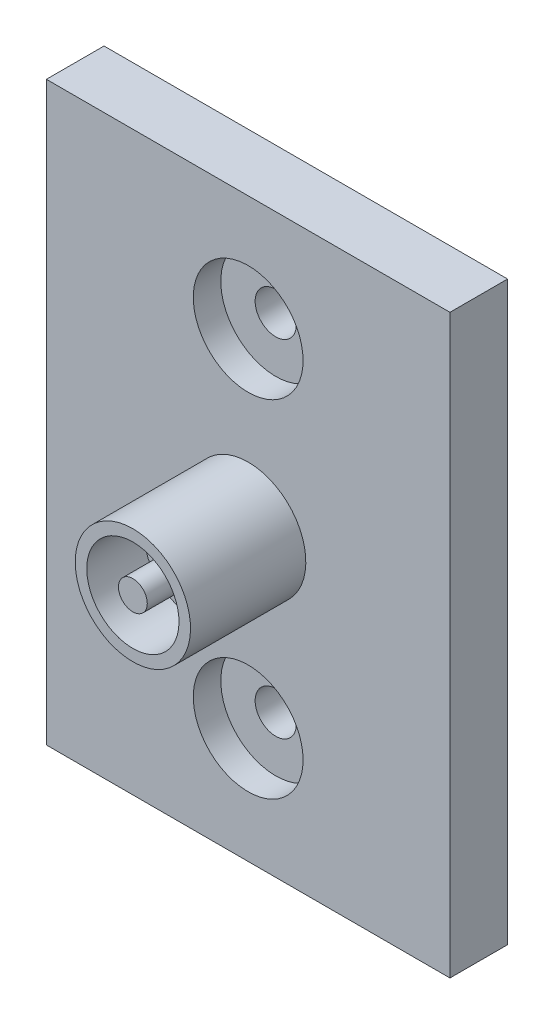
SolidWorks part; units mm, degrees
ref_plane "Front Plane" through (0, 0, 0) normal (0, 0, 1) x (1, 0, 0)
ref_plane "Top Plane" through (0, 0, 0) normal (0, 1, 0) x (1, 0, 0)
ref_plane "Right Plane" through (0, 0, 0) normal (1, 0, 0) x (0, 0, -1)
sketch "Sketch1" plane through (0, 0, 0) normal (0, 0, 1) x (1, 0, 0)
  line L1 (-35, -50) -> (35, -50)
  line L2 (-35, -50) -> (-35, 50)
  line L3 (-35, 50) -> (35, 50)
  line L4 (35, -50) -> (35, 50)
  line L5 (-35, -50) -> (35, 50) construction
  line L6 (-35, 50) -> (35, -50) construction
  point P0 (0, 0)
  dimension "D1" = 100
  dimension "D2" = 70
extrude "Boss-Extrude1" add sketch "Sketch1" along normal mid plane 10
sketch "Sketch2" plane through (0, 0, 5) normal (0, 0, 1) x (1, 0, 0)
  line L0 (16.5, 0) -> (-16.5, 0) construction
  circle A0 centre (0, 30) radius 4
  dimension "D1" = 30
  dimension "D2" = 8
sketch "Sketch3" plane through (0, 0, 5) normal (0, 0, 1) x (1, 0, 0)
  circle A0 centre (0, 0) radius 2.5
  dimension "D1" = 5
extrude "Boss-Extrude2" add sketch "Sketch3" along normal blind 20
sketch "Sketch5" plane through (0, 0, 0) normal (1, 0, 0) x (0, 0, -1)
  line L0 (-5, -50) -> (-5, 50) construction
  line L1 (-5, -50) -> (-5, 50) construction
  line L2 (-5, 6) -> (-15, 6)
  line L3 (-15, 6) -> (-15, 8)
  line L4 (-15, 8) -> (-25, 8)
  line L5 (-25, 8) -> (-25, 10)
  line L6 (-25, 10) -> (-5, 10)
  line L7 (-5, 10) -> (-5, 6)
  line L9 (0, 0) -> (-31.5999, 0) construction
  dimension "D1" = 12
  dimension "D2" = 2
  dimension "D3" = 2
  dimension "D4" = 10
  dimension "D5" = 10
revolve "Revolve1" add sketch "Sketch5" angle 360 about L9
hole_wizard "CBORE for 1/4 Hex Head Bolt1" positions "3DSketch1" profile "Sketch6" counterbore size "1/4" standard "ANSI Inch" end condition through all
sketch3d "3DSketch1"
  point P0 (0, 30, 5)
sketch "Sketch6" plane through (0, 30, 5) normal (1, 0, 0) x (0, -1, 0)
  line L0 (0, 0) -> (0, 10)
  line L1 (0, 10) -> (3.5712, 10)
  line L3 (3.5712, 10) -> (3.5712, 4.7752)
  line L4 (3.5712, 4.7752) -> (9.525, 4.7752)
  line L5 (9.525, 4.7752) -> (9.525, 0)
  line L7 (9.525, 0) -> (0, 0)
  line L11 (0, -6.35) -> (0, 107.95) construction
  dimension "Thru Hole Dia." = 7.1425
  dimension "Thru Hole Depth" = 10
  dimension "C'Bore Dia." = 19.05
  dimension "C'Bore Depth" = 4.7752
pattern_circular "CirPattern2" count 2 every 180 about axis through (0, 0, 0) along (0, 0, 1) of "CBORE for 1/4 Hex Head Bolt1"
ref_plane "Plane3" through (-5, 0, 0) normal (1, 0, 0) x (0, 0, -1)
sketch "Sketch8" plane through (-5, 0, 0) normal (1, 0, 0) x (0, 0, -1)
  circle A0 centre (-14.2393, 0) radius 1.5
  dimension "D1" = 3
extrude "Cut-Extrude2" cut sketch "Sketch8" against normal blind 10
